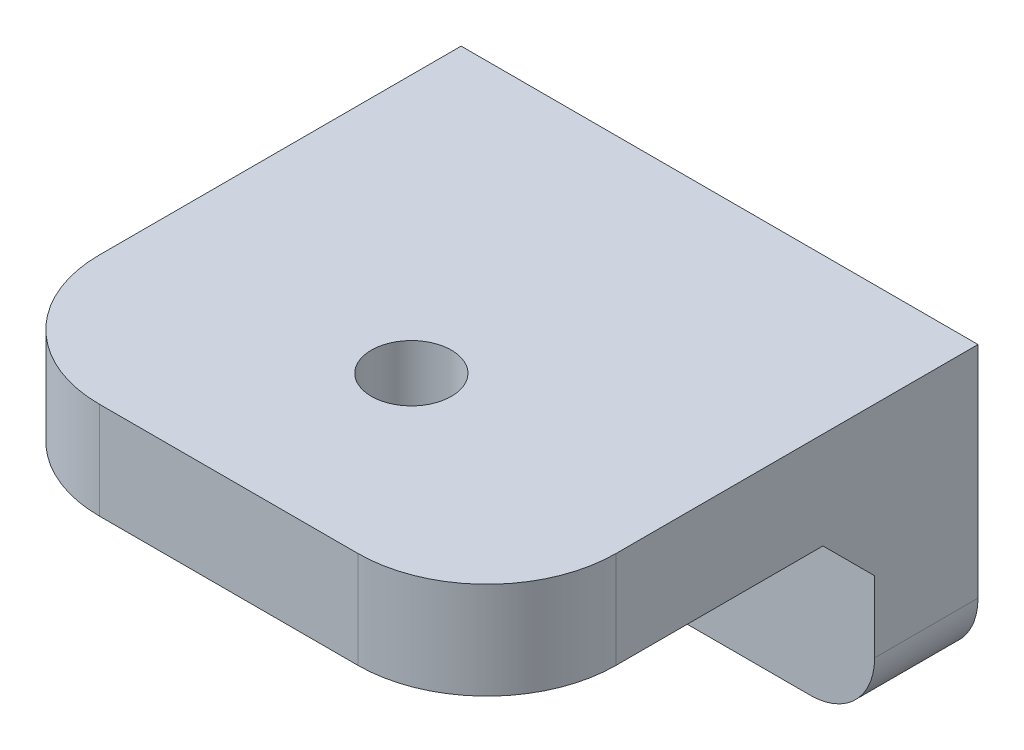
SolidWorks part; units mm, degrees
ref_plane "Front Plane" through (0, 0, 0) normal (0, 0, 1) x (1, 0, 0)
ref_plane "Top Plane" through (0, 0, 0) normal (0, 1, 0) x (1, 0, 0)
ref_plane "Right Plane" through (0, 0, 0) normal (1, 0, 0) x (0, 0, -1)
sketch "Sketch1" plane through (0, 0, 0) normal (0, 0, 1) x (1, 0, 0)
  line L1 (-20, -4.4065) -> (20, -4.4065)
  line L2 (-20, -4.4065) -> (-20, -26.4065)
  line L3 (-20, -26.4065) -> (20, -26.4065)
  line L4 (20, -4.4065) -> (20, -26.4065)
extrude "Boss-Extrude1" add sketch "Sketch1" along normal blind 8
sketch "Sketch2" plane through (0, 0, 8) normal (0, 0, 1) x (1, 0, 0)
  line L0 (20, -26.4065) -> (20, -4.4065) construction
  line L1 (-20, -4.4065) -> (20, -4.4065)
  line L2 (-20, -4.4065) -> (-20, -11.9065)
  line L3 (-20, -11.9065) -> (20, -11.9065)
  line L4 (20, -4.4065) -> (20, -11.9065)
  dimension "D1" = 7.5
extrude "Boss-Extrude2" add sketch "Sketch2" along normal blind 30
chamfer "Chamfer1" distance 4 angle 45 1 edges at (0, -11.9065, 8)
fillet "Fillet1" radius 10 2 edges at (20, -8.1565, 38) (-20, -8.1565, 38)
fillet "Fillet2" radius 5 2 edges at (20, -26.4065, 4) (-20, -26.4065, 4)
sketch "Sketch3" plane through (0, -4.4065, 0) normal (0, 1, 0) x (1, 0, 0)
  circle A0 centre (0, -23.8518) radius 3.1
extrude "Cut-Extrude1" cut sketch "Sketch3" against normal through all
